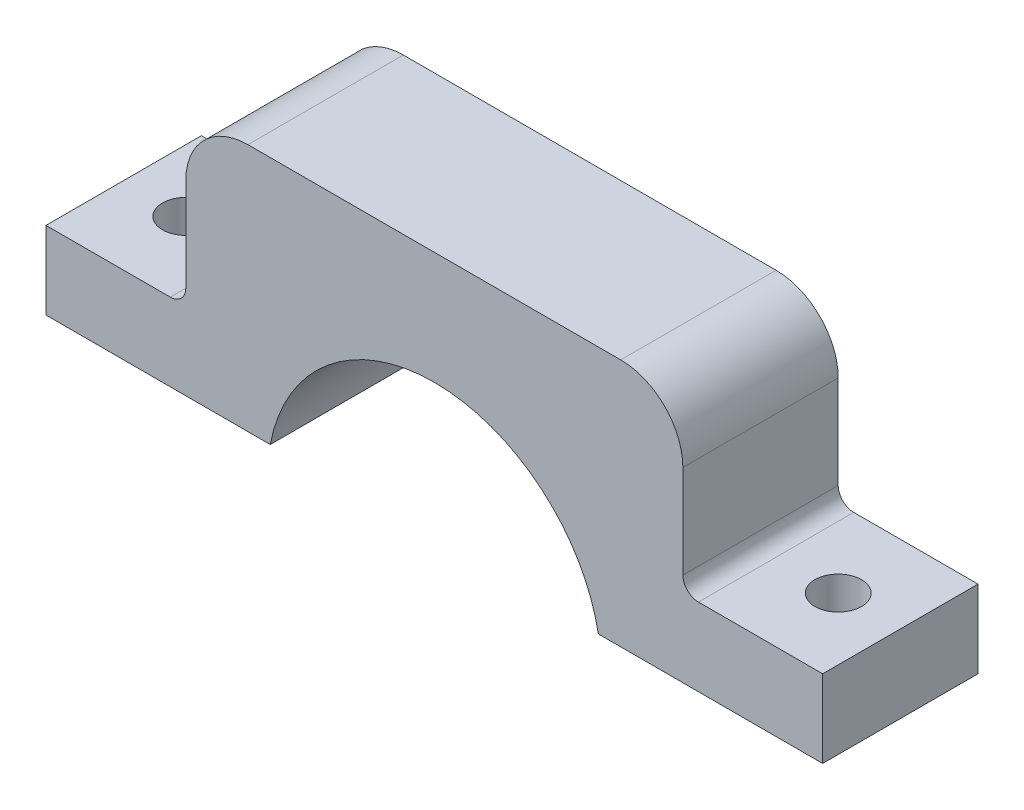
SolidWorks part; units mm, degrees
material "POM 乙缩醛共聚物"
ref_plane "前视基准面" through (0, 0, 0) normal (0, 0, 1) x (1, 0, 0)
ref_plane "上视基准面" through (0, 0, 0) normal (0, 1, 0) x (1, 0, 0)
ref_plane "右视基准面" through (0, 0, 0) normal (1, 0, 0) x (0, 0, -1)
sketch "草图1" plane through (0, 0, 0) normal (0, 0, 1) x (1, 0, 0)
  line L0 (0, 0) -> (18.1886, 0) construction
  line L1 (0, 0) -> (0, 14.725) construction
  line L2 (10.75, 0) -> (16, 0)
  line L3 (-10.75, 0) -> (-16, 0)
  line L4 (16, 0) -> (16, 18)
  line L5 (-16, 0) -> (-16, 18)
  line L6 (16, 18) -> (-16, 18)
  circle A0 centre (0, 0) radius 10.75
  point P12 (0, 18)
  dimension "D1" = 21.5
  dimension "D2" = 32
  dimension "D3" = 18
extrude "凸台-拉伸1" add sketch "草图1" along normal blind 10 contours A0 L2 L4 L6 L5 L3
sketch "草图3" plane through (0, 0, 10) normal (0, 0, 1) x (1, 0, 0)
  line L0 (16, 0) -> (16, 18) construction
  line L1 (-16, 0) -> (16, 0)
  line L2 (-16, 0) -> (-16, 2)
  line L3 (-16, 2) -> (16, 2)
  line L4 (16, 0) -> (16, 2)
  dimension "D1" = 2
extrude "切除-拉伸2" cut sketch "草图3" against normal through all
sketch "草图5" plane through (0, 0, 10) normal (0, 0, 1) x (1, 0, 0)
  line L0 (0, 18) -> (0, 0) construction
  line L1 (16, 18) -> (-16, 18) construction
  line L2 (25, 2) -> (25, 7)
  line L3 (-16, 2) -> (-25, 2)
  line L4 (-16, 2) -> (-16, 7)
  line L5 (-16, 7) -> (-25, 7)
  line L6 (-25, 2) -> (-25, 7)
  line L7 (16, 7) -> (25, 7)
  line L8 (16, 2) -> (16, 7)
  line L9 (16, 2) -> (25, 2)
  dimension "D1" = 9
  dimension "D2" = 5
extrude "凸台-拉伸2" add sketch "草图5" against normal up to surface (10 mm away) up to face at (0, 8.7917, 0)
fillet "圆角1" radius 1 2 edges at (16, 7, 5) (-16, 7, 5)
sketch "草图6" plane through (0, 7, 0) normal (0, 1, 0) x (1, 0, 0)
  line L0 (25, -5) -> (-25, -5) construction
  line L1 (25, 0) -> (25, -10) construction
  line L2 (-25, 0) -> (-25, -10) construction
  line L3 (0, -10) -> (0, 0) construction
  line L4 (16, -10) -> (-16, -10) construction
  circle A0 centre (21, -5) radius 1.5
  circle A1 centre (-21, -5) radius 1.5
  dimension "D1" = 4
  dimension "D2" = 3
extrude "切除-拉伸3" cut sketch "草图6" against normal through all
fillet "圆角2" radius 4 2 edges at (16, 18, 5) (-16, 18, 5)
